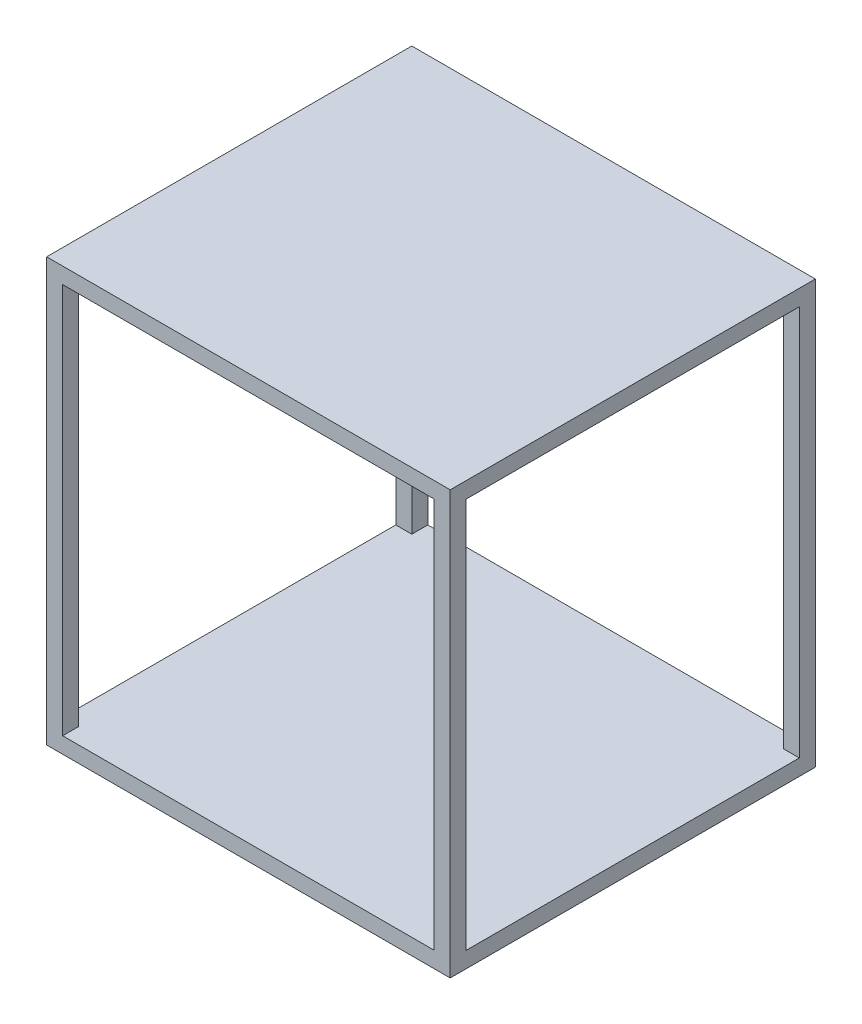
SolidWorks part; units mm, degrees
ref_plane "Front Plane" through (0, 0, 0) normal (0, 0, 1) x (1, 0, 0)
ref_plane "Top Plane" through (0, 0, 0) normal (0, 1, 0) x (1, 0, 0)
ref_plane "Right Plane" through (0, 0, 0) normal (1, 0, 0) x (0, 0, -1)
sketch "Sketch2" plane through (0, 0, 0) normal (0, 1, 0) x (1, 0, 0)
  line L1 (-315, 285) -> (315, 285)
  line L2 (-315, 285) -> (-315, -285)
  line L3 (-315, -285) -> (315, -285)
  line L4 (315, 285) -> (315, -285)
  line L5 (-315, 285) -> (315, -285) construction
  line L6 (-315, -285) -> (315, 285) construction
  point P0 (0, 0)
  dimension "D1" = 570
  dimension "D2" = 630
extrude "Boss-Extrude1" add sketch "Sketch2" along normal blind 660
sketch "Sketch4" plane through (0, 0, 285) normal (0, 0, 1) x (1, 0, 0)
  line L0 (-315, 0) -> (315, 0) construction
  line L1 (315, 660) -> (315, 0) construction
  line L2 (-315, 660) -> (315, 660) construction
  line L3 (-315, 660) -> (-315, 0) construction
  line L4 (-315, 0) -> (315, 0) construction
  line L5 (315, 660) -> (315, 0) construction
  line L6 (-315, 660) -> (315, 660) construction
  line L7 (-315, 660) -> (-315, 0) construction
  line L8 (-290, 25) -> (290, 25)
  line L9 (290, 635) -> (290, 25)
  line L10 (-290, 635) -> (290, 635)
  line L11 (-290, 635) -> (-290, 25)
  dimension "D1" = 25
extrude "Cut-Extrude1" cut sketch "Sketch4" against normal through all both and the other way through all
sketch "Sketch5" plane through (-315, 0, 0) normal (-1, 0, 0) x (0, 0, 1)
  line L0 (-285, 0) -> (285, 0) construction
  line L1 (285, 660) -> (285, 0) construction
  line L2 (-285, 660) -> (285, 660) construction
  line L3 (-285, 660) -> (-285, 0) construction
  line L4 (-285, 0) -> (285, 0) construction
  line L5 (285, 660) -> (285, 0) construction
  line L6 (-285, 660) -> (285, 660) construction
  line L7 (-285, 660) -> (-285, 0) construction
  line L8 (-260, 25) -> (260, 25)
  line L9 (260, 635) -> (260, 25)
  line L10 (-260, 635) -> (260, 635)
  line L11 (-260, 635) -> (-260, 25)
  dimension "D1" = 25
extrude "Cut-Extrude2" cut sketch "Sketch5" against normal through all both and the other way through all
